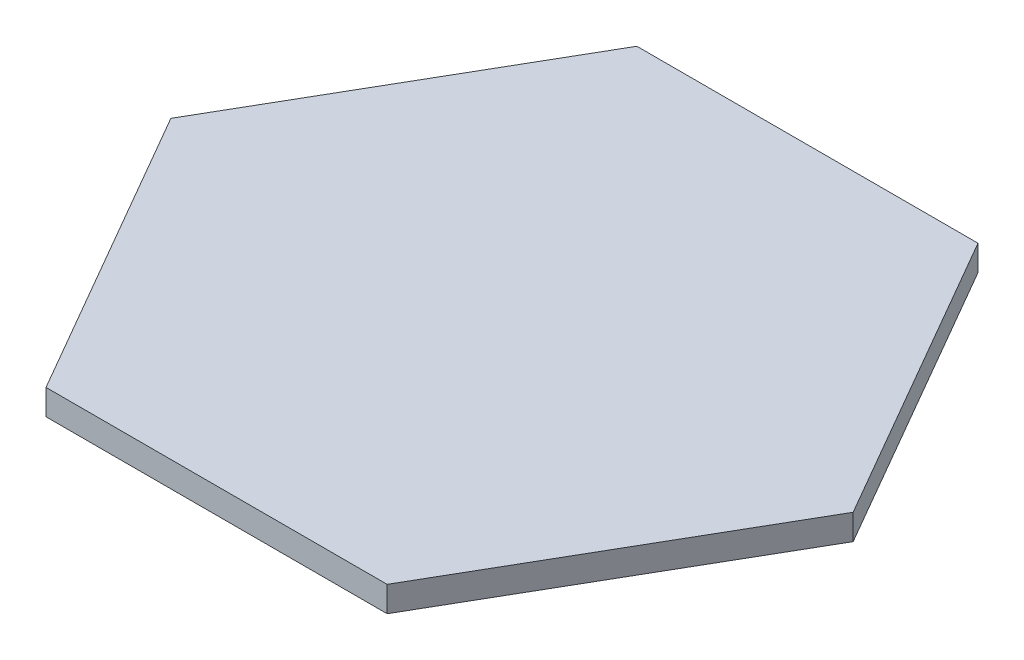
SolidWorks part; units mm, degrees
ref_plane "Front Plane" through (0, 0, 0) normal (0, 0, 1) x (1, 0, 0)
ref_plane "Top Plane" through (0, 0, 0) normal (0, 1, 0) x (1, 0, 0)
ref_plane "Right Plane" through (0, 0, 0) normal (1, 0, 0) x (0, 0, -1)
sketch "Gel Pad Pattern Sketch" plane through (0, 0, 0) normal (0, 1, 0) x (1, 0, 0)
  line L1 (-16.5, -28.5788) -> (16.5, -28.5788) construction
  line L2 (16.5, -28.5788) -> (33, 0) construction
  line L3 (33, 0) -> (16.5, 28.5788) construction
  line L4 (16.5, 28.5788) -> (-16.5, 28.5788) construction
  line L5 (-16.5, 28.5788) -> (-33, 0) construction
  line L6 (-33, 0) -> (-16.5, -28.5788) construction
  line L7 (-33, -57.1577) -> (33, -57.1577) construction
  line L8 (33, -57.1577) -> (66, 0) construction
  line L9 (66, 0) -> (33, 57.1577) construction
  line L10 (33, 57.1577) -> (-33, 57.1577) construction
  line L11 (-33, 57.1577) -> (-66, 0) construction
  line L12 (-66, 0) -> (-33, -57.1577) construction
  line L13 (-42.5263, -73.6577) -> (42.5263, -73.6577)
  line L14 (42.5263, -73.6577) -> (85.0526, 0)
  line L15 (85.0526, 0) -> (42.5263, 73.6577)
  line L16 (42.5263, 73.6577) -> (-42.5263, 73.6577)
  line L17 (-42.5263, 73.6577) -> (-85.0526, 0)
  line L18 (-85.0526, 0) -> (-42.5263, -73.6577)
  circle A0 centre (0, 0) radius 33 construction
  circle A1 centre (0, 0) radius 16.5 construction
  circle A2 centre (-16.5, 28.5788) radius 16.5 construction
  circle A3 centre (16.5, 28.5788) radius 16.5 construction
  circle A4 centre (33, 0) radius 16.5 construction
  circle A5 centre (16.5, -28.5788) radius 16.5 construction
  circle A6 centre (-16.5, -28.5788) radius 16.5 construction
  circle A7 centre (-33, 0) radius 16.5 construction
  circle A8 centre (0, 0) radius 57.1577 construction
  circle A9 centre (-49.5, 28.5788) radius 16.5 construction
  circle A10 centre (0, 57.1577) radius 16.5 construction
  circle A11 centre (49.5, 28.5788) radius 16.5 construction
  circle A12 centre (49.5, -28.5788) radius 16.5 construction
  circle A13 centre (0, -57.1577) radius 16.5 construction
  circle A14 centre (-49.5, -28.5788) radius 16.5 construction
  circle A15 centre (-66, 0) radius 16.5 construction
  circle A16 centre (-33, 57.1577) radius 16.5 construction
  circle A17 centre (33, 57.1577) radius 16.5 construction
  circle A18 centre (66, 0) radius 16.5 construction
  circle A19 centre (33, -57.1577) radius 16.5 construction
  circle A20 centre (-33, -57.1577) radius 16.5 construction
  circle A21 centre (0, 0) radius 73.6577 construction
  point P24 (0, 0)
  point P44 (0, 0)
  point P56 (0, 0)
  dimension "D1" = 66
  dimension "D2" = 33
  dimension "D4" = 33
  dimension "D5" = 6
  dimension "D3" = 6
  dimension "D6" = 6
extrude "Acrylic Base" add sketch "Gel Pad Pattern Sketch" along normal blind 6.35
